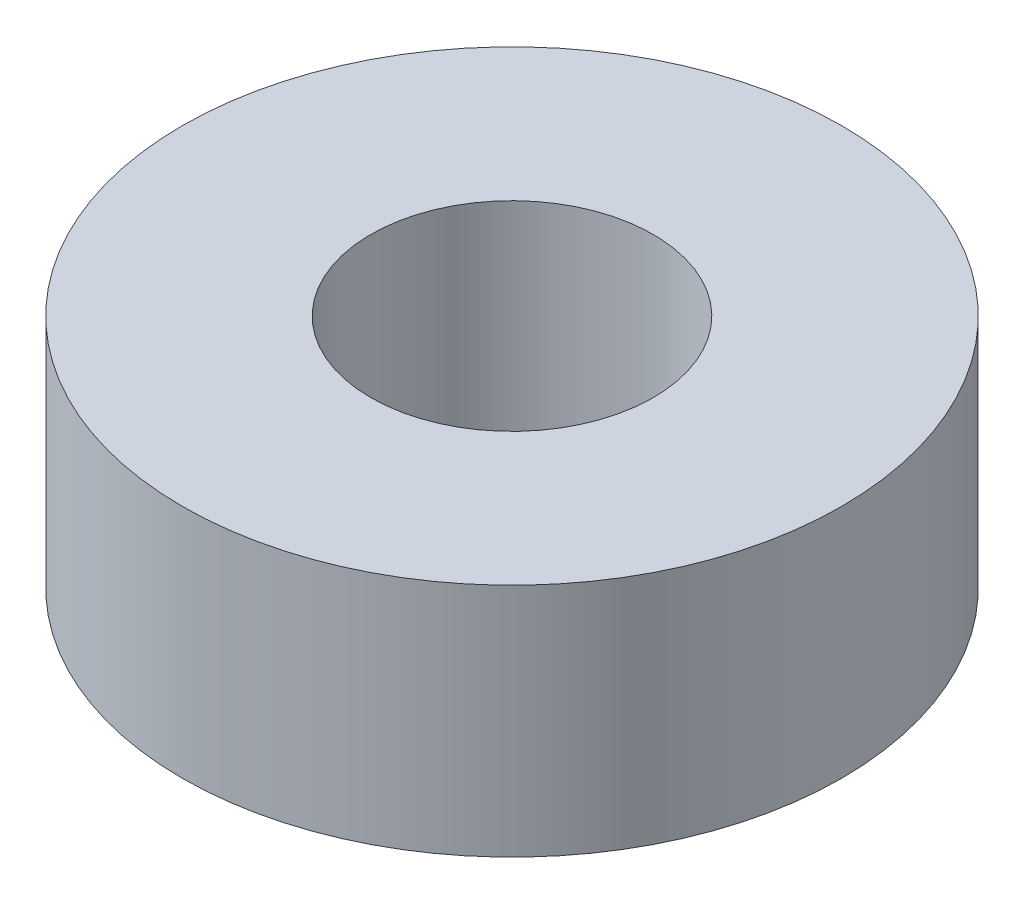
SolidWorks part; units mm, degrees
material "1060 合金"
ref_plane "前视基准面" through (0, 0, 0) normal (0, 0, 1) x (1, 0, 0)
ref_plane "上视基准面" through (0, 0, 0) normal (0, 1, 0) x (1, 0, 0)
ref_plane "右视基准面" through (0, 0, 0) normal (1, 0, 0) x (0, 0, -1)
sketch "草图1" plane through (0, 0, 0) normal (0, 1, 0) x (1, 0, 0)
  circle A0 centre (0, 0) radius 7
  circle A1 centre (0, 0) radius 3
  dimension "D1" = 6
  dimension "D2" = 14
extrude "凸台-拉伸1" add sketch "草图1" along normal blind 5
